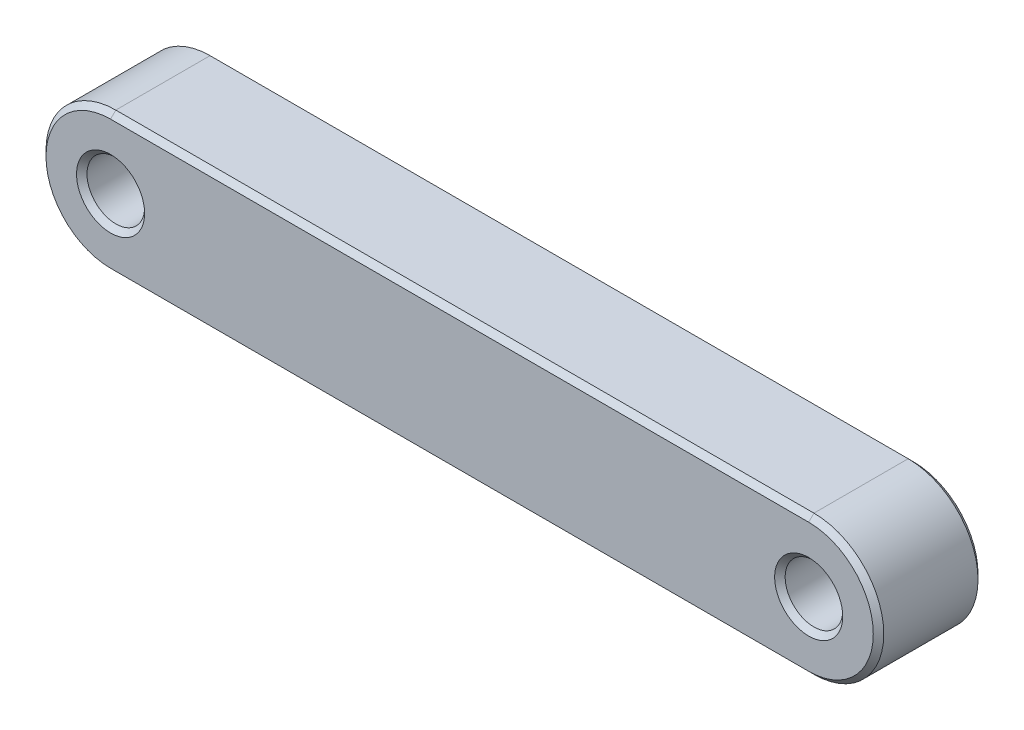
SolidWorks part; units mm, degrees
material "ABS"
ref_plane "Front Plane" through (0, 0, 0) normal (0, 0, 1) x (1, 0, 0)
ref_plane "Top Plane" through (0, 0, 0) normal (0, 1, 0) x (1, 0, 0)
ref_plane "Right Plane" through (0, 0, 0) normal (1, 0, 0) x (0, 0, -1)
sketch "Sketch1" plane through (0, 0, 0) normal (0, 0, 1) x (1, 0, 0)
  line L0 (-20, 0) -> (20, 0) construction
  line L5 (-20, 4) -> (20, 4)
  line L6 (-20, -4) -> (20, -4)
  arc A0 (-20, 4) -> (-20, -4) centre (-20, 0) ccw
  arc A1 (20, -4) -> (20, 4) centre (20, 0) ccw
  circle A2 centre (-20, 0) radius 1.65
  circle A3 centre (20, 0) radius 1.65
  point P2 (0, 0)
  dimension "D3" = 3.3
  dimension "D4" = 3.3
  dimension "D1" = 40
  dimension "D2" = 8
extrude "Boss-Extrude1" add sketch "Sketch1" along normal blind 6
hole_wizard "CSK for M3 Countersunk Flat Head Screw1" positions "Sketch2" profile "Sketch3" countersink size "M3" standard "ISO" end condition through all
sketch "Sketch2" plane through (0, 0, 0) normal (0, 0, 1) x (1, 0, 0)
  point P0 (-20, 0)
  point P3 (20, 0)
sketch "Sketch3" plane through (-20, 0, 0) normal (1, 0, 0) x (0, 1, 0)
  line L0 (0, 0) -> (0, 6)
  line L1 (0, 6) -> (1.65, 6)
  line L2 (1.65, 6) -> (1.65, 2)
  line L3 (1.65, 2) -> (3.15, 0.5)
  line L4 (3.15, 0.5) -> (3.15, 0)
  line L6 (3.15, 0) -> (0, 0)
  line L7 (-1.65, 2) -> (-3.15, 0.5) construction
  line L11 (0, -6.35) -> (0, 107.95) construction
  dimension "Thru Hole Dia." = 3.3
  dimension "Thru Hole Depth" = 6
  dimension "C'Sink Dia." = 6.3
  dimension "C'Sink Angle" = 90
  dimension "Head Clearance" = 0.5
chamfer "Chamfer1" distance 0.3 angle 45 10 edges at (0, -4, 0) (24, 0, 0) (0, 4, 0) (-24, 0, 0) (21.65, 0, 6) (0, 4, 6) (24, 0, 6) (0, -4, 6) (-24, 0, 6) (-18.35, 0, 6)
equation "\"D4@Sketch1\"=\"D3@Sketch1\""
